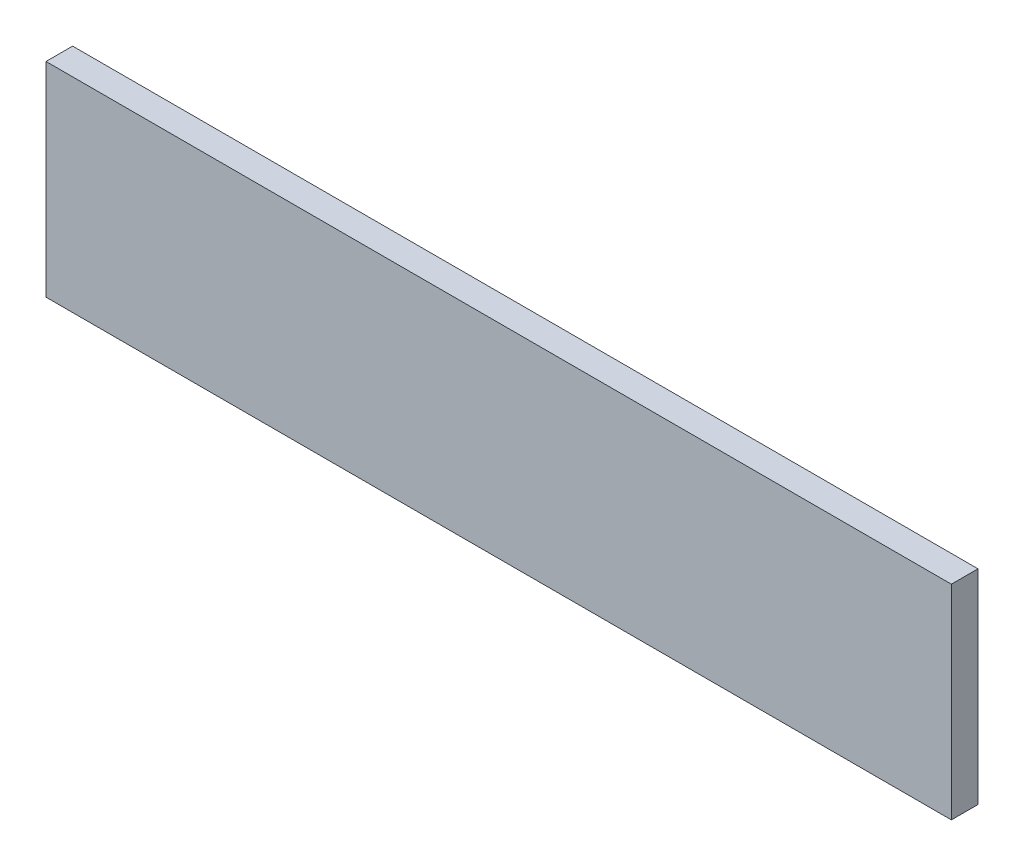
SolidWorks part; units mm, degrees
ref_plane "Front Plane" through (0, 0, 0) normal (0, 0, 1) x (1, 0, 0)
ref_plane "Top Plane" through (0, 0, 0) normal (0, 1, 0) x (1, 0, 0)
ref_plane "Right Plane" through (0, 0, 0) normal (1, 0, 0) x (0, 0, -1)
sketch "Sketch2" plane through (0, 0, 0) normal (0, 0, 1) x (1, 0, 0)
  line L1 (0, 0) -> (647.7, 0)
  line L2 (0, 0) -> (0, 146.05)
  line L3 (0, 146.05) -> (647.7, 146.05)
  line L4 (647.7, 0) -> (647.7, 146.05)
  dimension "D1" = 647.7
  dimension "D2" = 146.05
extrude "Boss-Extrude1" add sketch "Sketch2" along normal blind 19.05
